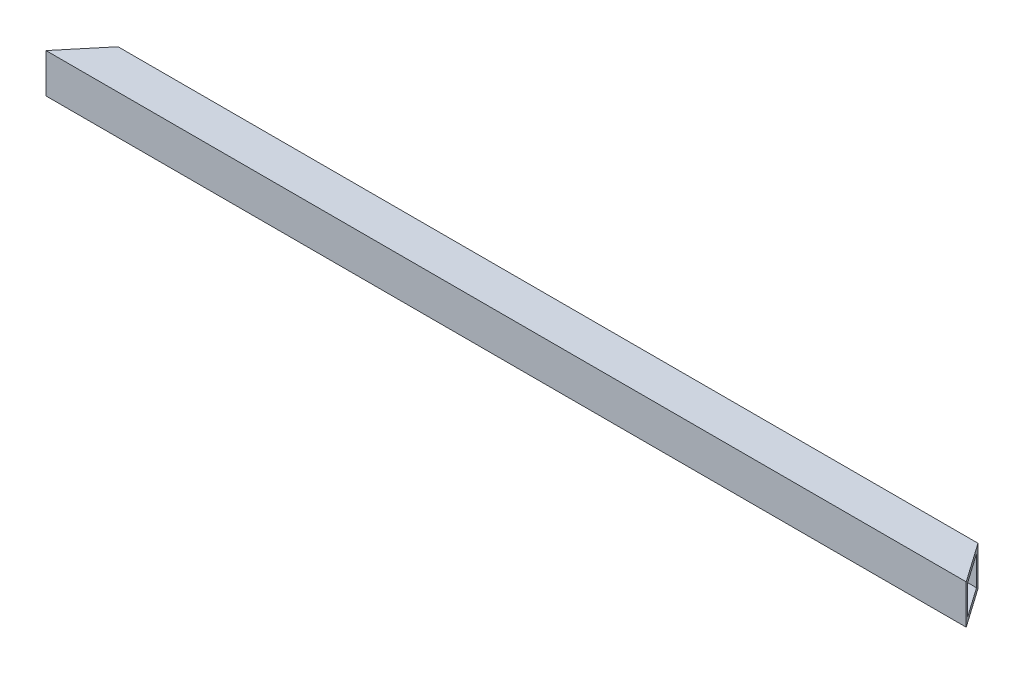
SolidWorks part; units mm, degrees
ref_plane "Front Plane" through (0, 0, 0) normal (0, 0, 1) x (1, 0, 0)
ref_plane "Top Plane" through (0, 0, 0) normal (0, 1, 0) x (1, 0, 0)
ref_plane "Right Plane" through (0, 0, 0) normal (1, 0, 0) x (0, 0, -1)
sketch "Sketch1" plane through (0, 0, 0) normal (1, 0, 0) x (0, 0, -1)
  line L0 (-4.7625, 4.7625) -> (4.7625, 4.7625)
  line L1 (-6.35, -6.35) -> (6.35, -6.35)
  line L2 (-6.35, -6.35) -> (-6.35, 6.35)
  line L3 (-6.35, 6.35) -> (6.35, 6.35)
  line L4 (6.35, -6.35) -> (6.35, 6.35)
  line L5 (-6.35, -6.35) -> (6.35, 6.35) construction
  line L6 (-6.35, 6.35) -> (6.35, -6.35) construction
  line L7 (4.7625, -4.7625) -> (4.7625, 4.7625)
  line L8 (-4.7625, -4.7625) -> (4.7625, -4.7625)
  line L9 (-4.7625, -4.7625) -> (-4.7625, 4.7625)
  dimension "D1" = 1.5875
extrude "Boss-Extrude1" add sketch "Sketch1" along normal mid plane 297.18
sketch "Sketch2" plane through (0, 0, 0) normal (0, 1, 0) x (1, 0, 0)
  line L0 (148.59, -6.35) -> (125.3463, 26.8454)
  line L1 (125.3463, 26.8454) -> (148.59, 26.8454)
  line L2 (148.59, 26.8454) -> (148.59, -6.35)
extrude "Cut-Extrude1" cut sketch "Sketch2" against normal through all and the other way through all
sketch "Sketch3" plane through (0, 0, 0) normal (0, 1, 0) x (1, 0, 0)
  line L0 (-138.0167, 6.35) -> (-148.59, -6.35)
  line L4 (-148.59, -6.35) -> (-148.59, 6.35)
  line L5 (-148.59, 6.35) -> (-138.0167, 6.35)
extrude "Cut-Extrude2" cut sketch "Sketch3" against normal through all and the other way through all
